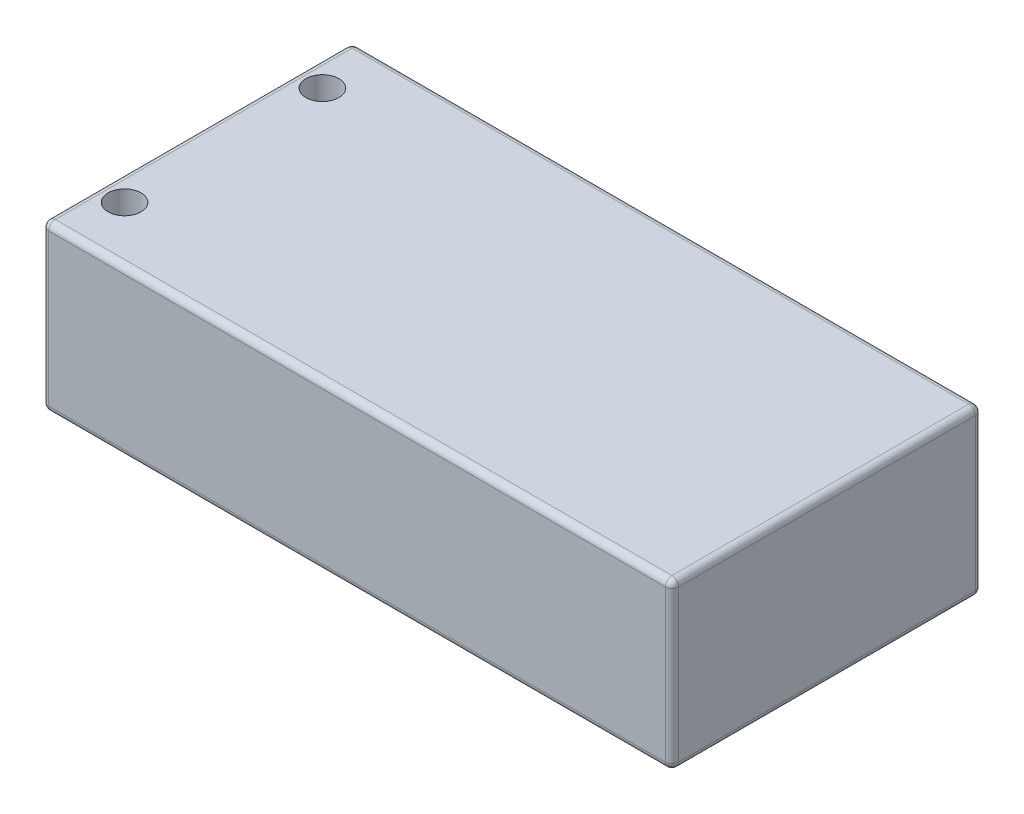
SolidWorks part; units mm, degrees
ref_plane "Front Plane" through (0, 0, 0) normal (0, 0, 1) x (1, 0, 0)
ref_plane "Top Plane" through (0, 0, 0) normal (0, 1, 0) x (1, 0, 0)
ref_plane "Right Plane" through (0, 0, 0) normal (1, 0, 0) x (0, 0, -1)
sketch "Sketch1" plane through (0, 0, 0) normal (0, 1, 0) x (1, 0, 0)
  line L1 (-47.75, -23.5) -> (47.75, -23.5)
  line L2 (-47.75, -23.5) -> (-47.75, 23.5)
  line L3 (-47.75, 23.5) -> (47.75, 23.5)
  line L4 (47.75, -23.5) -> (47.75, 23.5)
  line L5 (-47.75, -23.5) -> (47.75, 23.5) construction
  line L6 (-47.75, 23.5) -> (47.75, -23.5) construction
  point P0 (0, 0)
  dimension "D1" = 95.5
  dimension "D2" = 47
extrude "Boss-Extrude1" add sketch "Sketch1" along normal blind 25
sketch "Sketch2" plane through (0, 25, 0) normal (0, 1, 0) x (1, 0, 0)
  line L1 (47.75, 23.5) -> (-47.75, 23.5) construction
  line L2 (-47.75, 23.5) -> (-47.75, -23.5) construction
  circle A0 centre (-43.75, 15) radius 2.5
  circle A1 centre (-43.75, -15) radius 2.5
  dimension "D3" = 5
  dimension "D1" = 30
  dimension "D2" = 8.5
  dimension "D4" = 4
extrude "Cut-Extrude1" cut sketch "Sketch2" against normal blind 20
fillet "Fillet1" radius 1 12 edges at (47.75, 12.5, 23.5) (47.75, 12.5, -23.5) (-47.75, 12.5, -23.5) (-47.75, 12.5, 23.5) (0, 0, -23.5) (-47.75, 0, 0) (0, 0, 23.5) (47.75, 0, 0) (0, 25, 23.5) (-47.75, 25, 0) (0, 25, -23.5) (47.75, 25, 0)
equation "\"D2@Sketch2\"=(47-\"D1@Sketch2\")/2"
